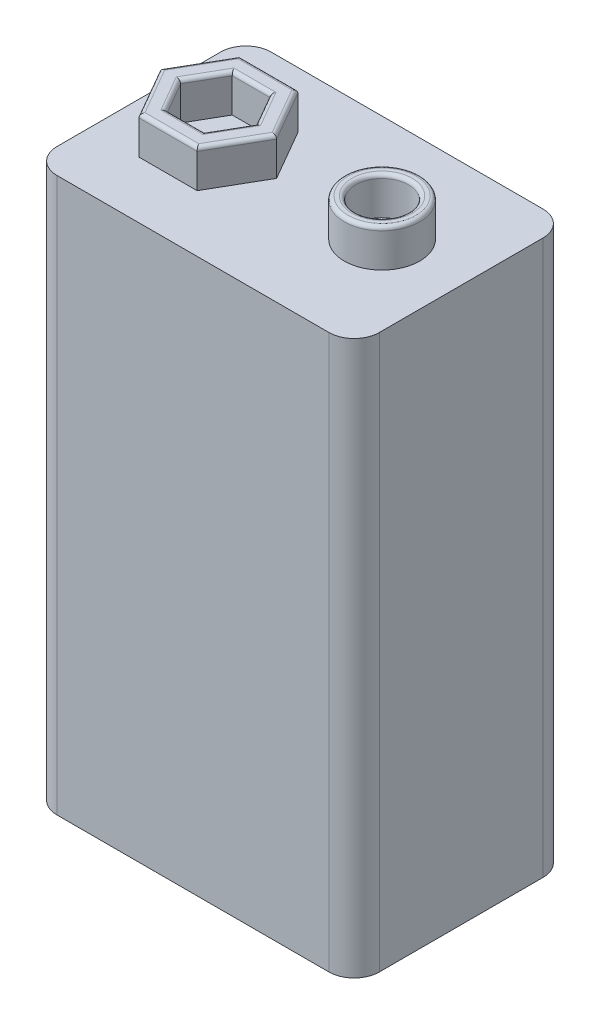
SolidWorks part; units mm, degrees
ref_plane "Спереди" through (0, 0, 0) normal (0, 0, 1) x (1, 0, 0)
ref_plane "Сверху" through (0, 0, 0) normal (0, 1, 0) x (1, 0, 0)
ref_plane "Справа" through (0, 0, 0) normal (1, 0, 0) x (0, 0, -1)
sketch "Эскиз1" plane through (0, 0, 0) normal (0, 1, 0) x (1, 0, 0)
  line L1 (-12.8, -8.5) -> (12.8, -8.5)
  line L2 (-12.8, -8.5) -> (-12.8, 8.5)
  line L3 (-12.8, 8.5) -> (12.8, 8.5)
  line L4 (12.8, -8.5) -> (12.8, 8.5)
  line L5 (-12.8, -8.5) -> (12.8, 8.5) construction
  line L6 (-12.8, 8.5) -> (12.8, -8.5) construction
  point P0 (0, 0)
  dimension "D1" = 25.6
  dimension "D2" = 17
extrude "Бобышка-Вытянуть1" add sketch "Эскиз1" along normal blind 44
fillet "Скругление1" radius 2 4 edges at (12.8, 22, -8.5) (12.8, 22, 8.5) (-12.8, 22, -8.5) (-12.8, 22, 8.5)
sketch "Эскиз2" plane through (0, 44, 0) normal (0, 1, 0) x (1, 0, 0)
  line L0 (-1.8835, 0.0209) -> (-4.1929, 4.0209)
  line L1 (-4.1929, 4.0209) -> (-8.8117, 4.0209)
  line L2 (-8.8117, 4.0209) -> (-11.1211, 0.0209)
  line L3 (-11.1211, 0.0209) -> (-8.8117, -3.9791)
  line L4 (-8.8117, -3.9791) -> (-4.1929, -3.9791)
  line L5 (-4.1929, -3.9791) -> (-1.8835, 0.0209)
  line L6 (-3.5001, 0.0209) -> (-5.0012, 2.6209)
  line L7 (-5.0012, 2.6209) -> (-8.0034, 2.6209)
  line L8 (-8.0034, 2.6209) -> (-9.5046, 0.0209)
  line L9 (-9.5046, 0.0209) -> (-8.0034, -2.5791)
  line L10 (-8.0034, -2.5791) -> (-5.0012, -2.5791)
  line L11 (-5.0012, -2.5791) -> (-3.5001, 0.0209)
  line L12 (-6.5023, 0.0209) -> (6.4977, 0.0209) construction
  circle A0 centre (6.4977, 0.0209) radius 3
  circle A1 centre (6.4977, 0.0209) radius 2.1
  circle A2 centre (-6.5023, 0.0209) radius 4 construction
  circle A3 centre (-6.5023, 0.0209) radius 2.6 construction
  point P18 (0, 0)
  dimension "D1" = 6
  dimension "D2" = 4.2
  dimension "D3" = 8
  dimension "D4" = 5.2
  dimension "D5" = 13
extrude "Бобышка-Вытянуть2" add sketch "Эскиз2" along normal blind 3
fillet "Скругление2" radius 0.3 14 edges at (6.4977, 47, 2.0791) (6.4977, 47, 2.9791) (-6.5023, 47, -2.6209) (-8.754, 47, -1.3209) (-8.754, 47, 1.2791) (-6.5023, 47, 2.5791) (-4.2507, 47, 1.2791) (-4.2507, 47, -1.3209) (-6.5023, 47, 3.9791) (-9.9664, 47, 1.9791) (-9.9664, 47, -2.0209) (-6.5023, 47, -4.0209) (-3.0382, 47, -2.0209) (-3.0382, 47, 1.9791)
